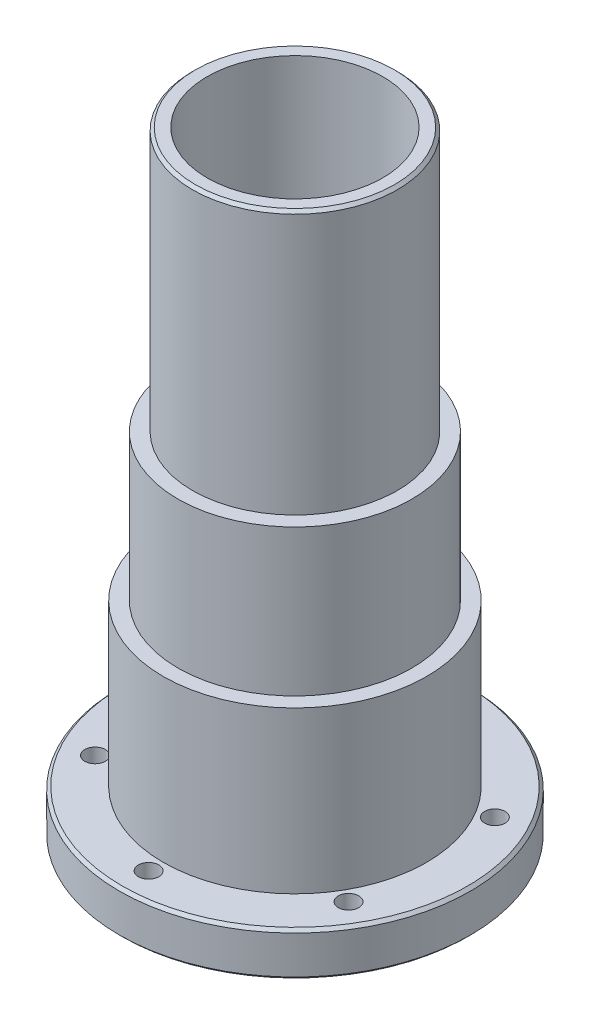
SolidWorks part; units mm, degrees
material "6061 合金"
ref_plane "前视基准面" through (0, 0, 0) normal (0, 0, 1) x (1, 0, 0)
ref_plane "上视基准面" through (0, 0, 0) normal (0, 1, 0) x (1, 0, 0)
ref_plane "右视基准面" through (0, 0, 0) normal (1, 0, 0) x (0, 0, -1)
sketch "草图1" plane through (0, 0, 0) normal (1, 0, 0) x (0, 0, -1)
  line L0 (0, 44) -> (0, 0) construction
  line L1 (-15, 105) -> (-15, 0)
  line L2 (-15, 0) -> (-30, 0)
  line L3 (-30, 0) -> (-30, 7.5)
  line L4 (-30, 7.5) -> (-22.5, 7.5)
  line L5 (-22.5, 7.5) -> (-22.5, 35)
  line L6 (-22.5, 35) -> (-20, 35)
  line L7 (-20, 35) -> (-20, 60)
  line L8 (-20, 60) -> (-17.5, 60)
  line L9 (-17.5, 60) -> (-17.5, 105)
  line L10 (-17.5, 105) -> (-15, 105)
  dimension "D1" = 30
  dimension "D2" = 60
  dimension "D3" = 45
  dimension "D4" = 40
  dimension "D5" = 35
  dimension "D6" = 105
  dimension "D7" = 7.5
  dimension "D8" = 45
  dimension "D9" = 25
revolve "旋转1" add sketch "草图1" angle 360 about L0
hole_wizard "打孔尺寸(%根据)内六角圆柱头螺钉的类型1" positions "草图4" profile "草图5" counterbore size "M3" standard "GB" end condition through all
sketch "草图4" plane through (0, 0, 0) normal (0, -1, 0) x (-1, 0, 0)
  point P0 (0, -25)
  dimension "D1" = 25
sketch "草图5" plane through (0, 0, 25) normal (1, 0, 0) x (0, 0, -1)
  line L0 (0, 0) -> (0, 105)
  line L1 (0, 105) -> (1.75, 105)
  line L3 (1.75, 105) -> (1.75, 4)
  line L4 (1.75, 4) -> (3, 4)
  line L5 (3, 4) -> (3, 0)
  line L7 (3, 0) -> (0, 0)
  line L11 (0, -6.35) -> (0, 107.95) construction
  dimension "通孔孔直径" = 3.5
  dimension "通孔孔深度" = 105
  dimension "柱形沉头孔直径" = 6
  dimension "柱形沉头孔深度" = 4
pattern_circular "阵列(圆周)1" count 6 over 360 about axis through (0, 0, 0) along (0, 1, 0) of "打孔尺寸(%根据)内六角圆柱头螺钉的类型1"
chamfer "倒角1" distance 0.5 angle 45 3 edges at (0, 7.5, 30) (0, 0, 30) (0, 105, 17.5)
